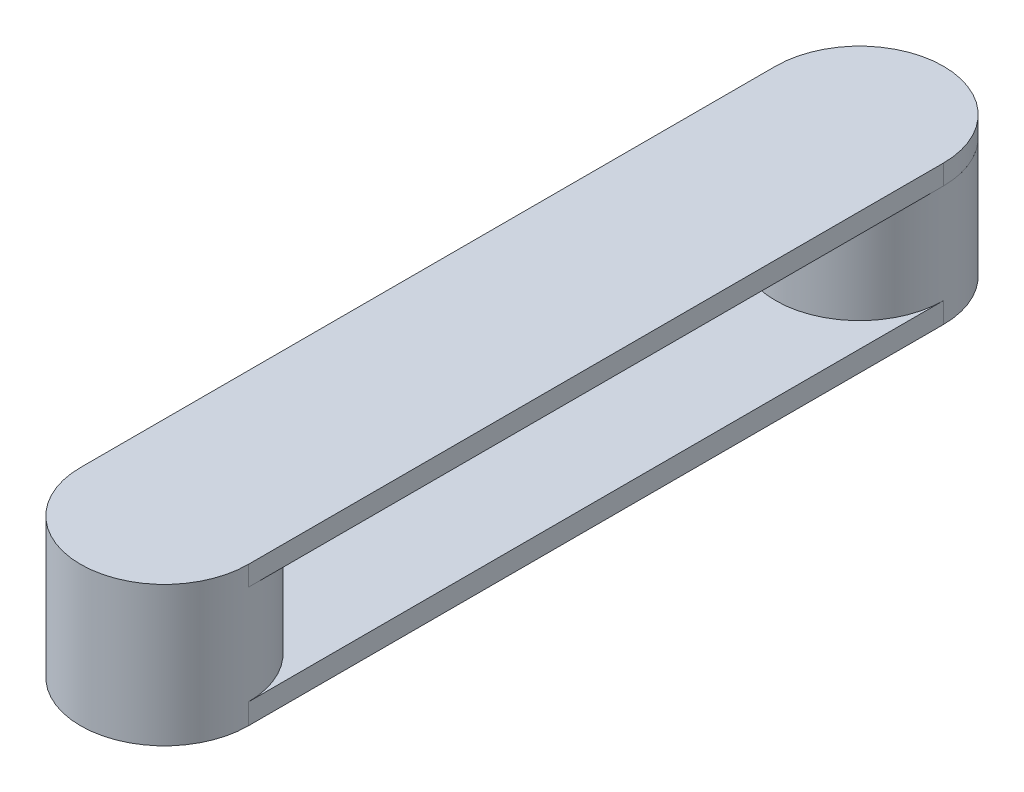
SolidWorks part; units mm, degrees
ref_plane "Front Plane" through (0, 0, 0) normal (0, 0, 1) x (1, 0, 0)
ref_plane "Top Plane" through (0, 0, 0) normal (0, 1, 0) x (1, 0, 0)
ref_plane "Right Plane" through (0, 0, 0) normal (1, 0, 0) x (0, 0, -1)
sketch "Sketch3" plane through (0, 0, 0) normal (0, 1, 0) x (1, 0, 0)
  line L0 (84.5, 140.3468) -> (-84.5, 140.3468)
  line L1 (84.5, 140.3468) -> (84.5, 840.3468)
  line L2 (-84.5, 140.3468) -> (-84.5, 840.3468)
  line L3 (84.5, 840.3468) -> (-84.5, 840.3468)
  circle A0 centre (0, 140.3468) radius 84.5
  circle A1 centre (0, 840.3468) radius 84.5
extrude "Boss-Extrude3" add sketch "Sketch3" along normal blind 19.8444 and the other way blind 1 contours L0 A0 | L0 A0 | A1 L2 A0 L1 | L3 A1 | L3 A1
sketch "Sketch4" plane through (0, 19.8444, 0) normal (0, 1, 0) x (1, 0, 0)
  circle A0 centre (0, 140.3468) radius 84.5
extrude "Boss-Extrude4" add sketch "Sketch4" along normal blind 100
sketch "Sketch5" plane through (0, 19.8444, 0) normal (0, 1, 0) x (1, 0, 0)
  line L0 (102.8704, 421.8863) -> (-72.5213, 421.8863)
  line L1 (102.8704, 421.8863) -> (102.8704, 1121.8863)
  line L2 (-72.5213, 421.8863) -> (-72.5213, 1121.8863)
  line L3 (102.8704, 1121.8863) -> (-72.5213, 1121.8863)
  circle A0 centre (15.1745, 421.8863) radius 87.6958
  circle A1 centre (15.1745, 1121.8863) radius 87.6958
sketch "Sketch6" plane through (0, 19.8444, 0) normal (0, 1, 0) x (1, 0, 0)
  circle A0 centre (0, 840.3468) radius 84.5
extrude "Boss-Extrude6" add sketch "Sketch6" along normal blind 100
sketch "Sketch7" plane through (0, 119.8444, 0) normal (0, 1, 0) x (1, 0, 0)
  line L0 (84.5, 140.3468) -> (-84.5, 140.3468)
  line L1 (84.5, 140.3468) -> (84.5, 840.3289)
  line L2 (-84.5, 140.3468) -> (-84.5, 840.3289)
  line L3 (84.5, 840.3289) -> (-84.5, 840.3289)
  circle A0 centre (0, 140.3468) radius 84.5
  circle A1 centre (0, 840.3289) radius 84.5
  circle M1 centre (0, 140.3468) radius 84.5
extrude "Boss-Extrude7" add sketch "Sketch7" along normal blind 20 contours L0 M1 | L0 M1 | A1 L2 L1 M1 | L3 A1 | L3 A1
